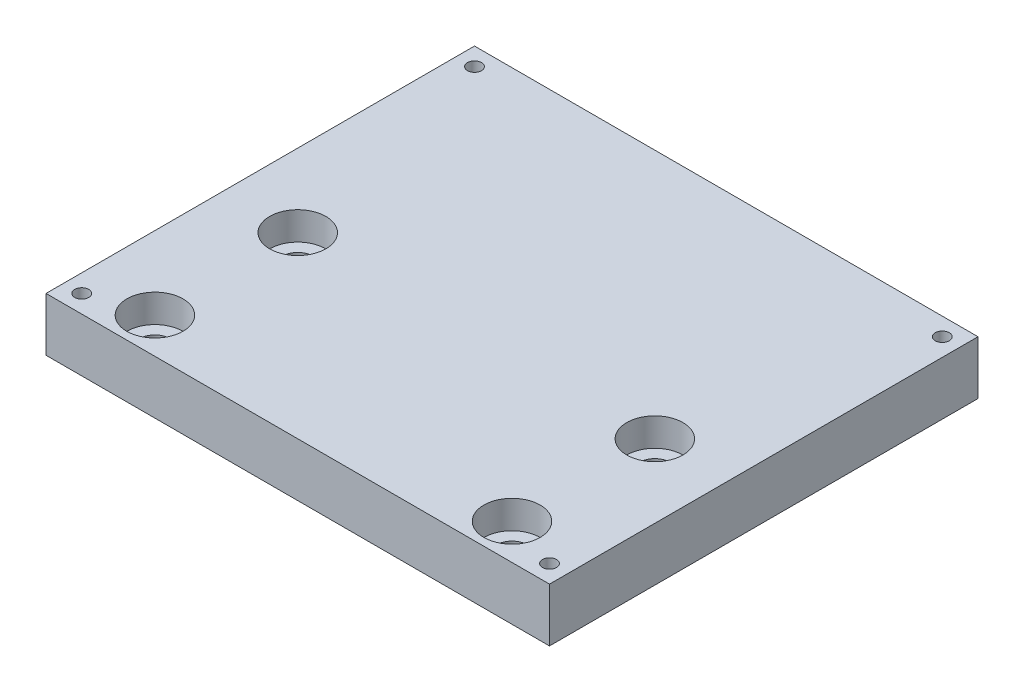
SolidWorks part; units mm, degrees
ref_plane "Front" through (0, 0, 0) normal (0, 0, 1) x (1, 0, 0)
ref_plane "Top" through (0, 0, 0) normal (0, 1, 0) x (1, 0, 0)
ref_plane "Right" through (0, 0, 0) normal (1, 0, 0) x (0, 0, -1)
sketch "Sketch1" plane through (0, 0, 0) normal (0, 1, 0) x (1, 0, 0)
  line L1 (-44.7675, -38.1) -> (44.7675, -38.1)
  line L2 (-44.7675, -38.1) -> (-44.7675, 38.1)
  line L3 (-44.7675, 38.1) -> (44.7675, 38.1)
  line L4 (44.7675, -38.1) -> (44.7675, 38.1)
  line L5 (-44.7675, -38.1) -> (44.7675, 38.1) construction
  line L6 (-44.7675, 38.1) -> (44.7675, -38.1) construction
  point P0 (0, 0)
  dimension "D1" = 89.535
  dimension "D2" = 76.2
extrude "Extrude1" add sketch "Sketch1" along normal blind 9.525
sketch "Sketch7" plane through (0, 9.525, 0) normal (0, 1, 0) x (-1, 0, 0)
  line L0 (0, -50.9127) -> (0, 42.3442) construction
hole_wizard "CBORE for M5 SHCS3" positions "3DSketch5" profile "Sketch8" counterbore size "M5" standard "Ansi Metric" end condition through all
sketch3d "3DSketch5"
  line L0 (-44.7675, 9.525, 38.1) -> (44.7675, 9.525, 38.1) construction
  line L1 (0, 9.525, -50.9127) -> (0, 9.525, 42.3442) construction
  point P0 (-31.75, 9.525, 31.75)
  dimension "D1" = 6.35
  dimension "D2" = 31.75
sketch "Sketch8" plane through (-31.75, 9.525, 31.75) normal (1, 0, 0) x (0, 0, 1)
  line L0 (0, 0) -> (0, 9.525)
  line L1 (0, 9.525) -> (2.75, 9.525)
  line L3 (2.75, 9.525) -> (2.75, 5)
  line L4 (2.75, 5) -> (5, 5)
  line L5 (5, 5) -> (5, 0)
  line L7 (5, 0) -> (0, 0)
  line L11 (0, -6.35) -> (0, 107.95) construction
  dimension "Thru Hole Dia." = 5.5
  dimension "Thru Hole Depth" = 9.525
  dimension "C'Bore Dia." = 10
  dimension "C'Bore Depth" = 5
sketch "Sketch9" plane through (0, 9.525, 0) normal (0, 1, 0) x (-1, 0, 0)
  line L0 (57.0939, 31.75) -> (-64.265, 31.75) construction
sketch "Sketch10" plane through (0, 9.525, 0) normal (0, 1, 0) x (-1, 0, 0)
  line L0 (31.75, 41.5855) -> (31.75, -17.6832) construction
pattern_linear "LPattern4" count 2 spacing 63.5 along (1, 0, 0) count 2 spacing 25.4 along (0, 0, -1) of "CBORE for M5 SHCS3"
hole_wizard "M3x0.5 Tapped Hole2" positions "3DSketch6" profile "Sketch11" tap size "M3x0.5" standard "Ansi Metric" end condition through all
sketch3d "3DSketch6"
  line L0 (-44.7675, 9.525, 38.1) -> (44.7675, 9.525, 38.1) construction
  line L1 (-44.7675, 9.525, -38.1) -> (-44.7675, 9.525, 38.1) construction
  point P0 (-41.5925, 9.525, 34.925)
  dimension "D1" = 3.175
  dimension "D2" = 3.175
sketch "Sketch11" plane through (-41.5925, 9.525, 34.925) normal (1, 0, 0) x (0, 0, 1)
  line L0 (0, 0) -> (0, 9.525)
  line L1 (0, 9.525) -> (1.25, 9.525)
  line L2 (1.25, 9.525) -> (1.25, 0)
  line L5 (1.25, 0) -> (0, 0)
  line L11 (0, -6.35) -> (0, 107.95) construction
  dimension "Thread Major Dia." = 2.5
  dimension "Thru Tap Drill Depth" = 9.525
pattern_linear "LPattern5" count 2 spacing 83.185 along (1, 0, 0) count 2 spacing 69.85 along (0, 0, -1) of "M3x0.5 Tapped Hole2"
